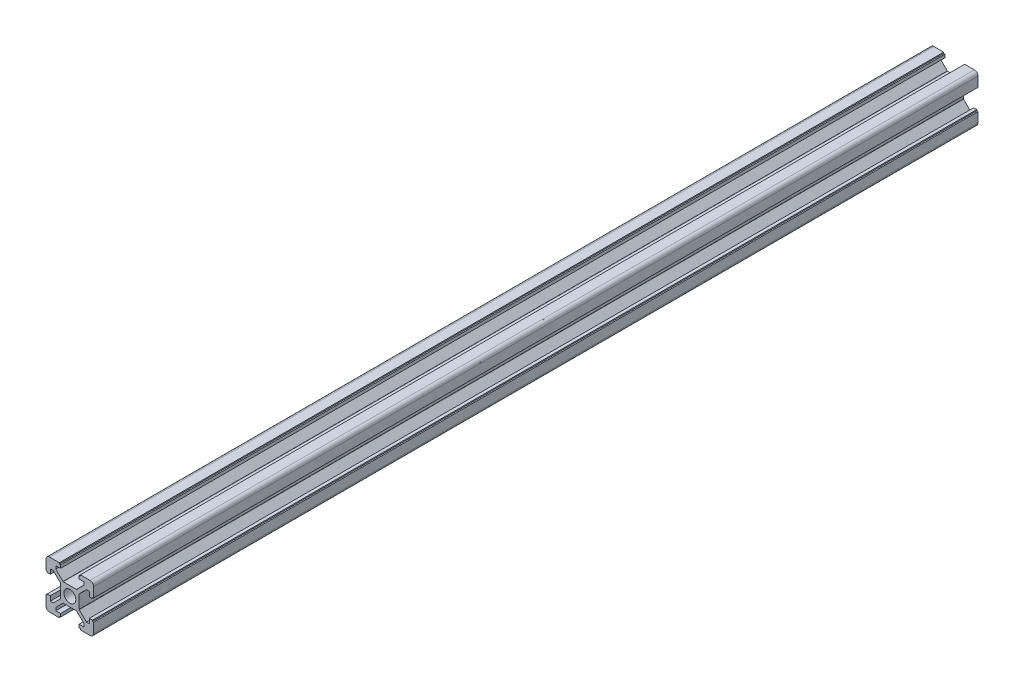
SolidWorks part; units mm, degrees
ref_plane "前视基准面" through (0, 0, 0) normal (0, 0, 1) x (1, 0, 0)
ref_plane "上视基准面" through (0, 0, 0) normal (0, 1, 0) x (1, 0, 0)
ref_plane "右视基准面" through (0, 0, 0) normal (1, 0, 0) x (0, 0, -1)
other "Configuration Table"
sketch "草图1" plane through (0, 0, 0) normal (0, 0, 1) x (1, 0, 0)
  line L0 (-10, 0) -> (10, 0) construction
  line L1 (-10, 10) -> (-4.4, 10)
  line L2 (-10, 10) -> (-10, 4.4)
  line L3 (-10, -10) -> (-4.4, -10)
  line L4 (10, 10) -> (10, 4.4)
  line L5 (-10, 10) -> (10, -10) construction
  line L6 (-10, -10) -> (10, 10) construction
  line L7 (-2.8396, 3.9001) -> (2.8395, 3.9001)
  line L8 (-3.9, 2.8393) -> (-3.9, -2.8395)
  line L9 (-2.8393, -3.9) -> (2.8395, -3.9)
  line L10 (3.9001, 2.8396) -> (3.9001, -2.8395)
  line L11 (-3.9, 3.9) -> (3.9, -3.9) construction
  line L12 (-3.9, -3.9) -> (3.9, 3.9) construction
  line L13 (0, 10) -> (0, -10) construction
  line L14 (-6.9607, 5.9) -> (-3.9, 2.8393)
  line L15 (-5.9, 6.9607) -> (-2.8396, 3.9001)
  line L16 (-6.9607, 5.9) -> (-8.2, 5.9)
  line L17 (-8.2, 5.9) -> (-8.2, 3.9)
  line L18 (-8.2, 3.9) -> (-9.5, 3.9)
  line L19 (-9.5, 3.9) -> (-9.5, 4.4)
  line L20 (-9.5, 4.4) -> (-10, 4.4)
  line L21 (-5.9, 6.9607) -> (-5.9, 8.2)
  line L22 (-5.9, 8.2) -> (-3.9, 8.2)
  line L23 (-3.9, 8.2) -> (-3.9, 9.5)
  line L24 (-3.9, 9.5) -> (-4.4, 9.5)
  line L25 (-4.4, 9.5) -> (-4.4, 10)
  line L26 (6.9607, 5.9) -> (3.9001, 2.8396)
  line L27 (5.9, 6.9607) -> (2.8393, 3.9)
  line L28 (5.9, 6.9607) -> (5.9, 8.2)
  line L29 (5.9, 8.2) -> (3.9, 8.2)
  line L30 (3.9, 8.2) -> (3.9, 9.5)
  line L31 (3.9, 9.5) -> (4.4, 9.5)
  line L32 (4.4, 9.5) -> (4.4, 10)
  line L33 (6.9607, 5.9) -> (8.2, 5.9)
  line L34 (8.2, 5.9) -> (8.2, 3.9)
  line L35 (8.2, 3.9) -> (9.5, 3.9)
  line L36 (9.5, 3.9) -> (9.5, 4.4)
  line L37 (9.5, 4.4) -> (10, 4.4)
  line L38 (5.9, -6.9607) -> (2.8395, -3.9)
  line L39 (6.9607, -5.9) -> (3.9, -2.8393)
  line L40 (6.9607, -5.9) -> (8.2, -5.9)
  line L41 (8.2, -5.9) -> (8.2, -3.9)
  line L42 (8.2, -3.9) -> (9.5, -3.9)
  line L43 (9.5, -3.9) -> (9.5, -4.4)
  line L44 (9.5, -4.4) -> (10, -4.4)
  line L45 (5.9, -6.9607) -> (5.9, -8.2)
  line L46 (5.9, -8.2) -> (3.9, -8.2)
  line L47 (3.9, -8.2) -> (3.9, -9.5)
  line L48 (3.9, -9.5) -> (4.4, -9.5)
  line L49 (4.4, -9.5) -> (4.4, -10)
  line L50 (-6.9607, -5.9) -> (-3.9, -2.8395)
  line L51 (-5.9, -6.9607) -> (-2.8393, -3.9)
  line L52 (-5.9, -6.9607) -> (-5.9, -8.2)
  line L53 (-5.9, -8.2) -> (-3.9, -8.2)
  line L54 (-3.9, -8.2) -> (-3.9, -9.5)
  line L55 (-3.9, -9.5) -> (-4.4, -9.5)
  line L56 (-4.4, -9.5) -> (-4.4, -10)
  line L57 (-6.9607, -5.9) -> (-8.2, -5.9)
  line L58 (-8.2, -5.9) -> (-8.2, -3.9)
  line L59 (-8.2, -3.9) -> (-9.5, -3.9)
  line L60 (-9.5, -3.9) -> (-9.5, -4.4)
  line L61 (-9.5, -4.4) -> (-10, -4.4)
  line L62 (4.4, -10) -> (10, -10)
  line L63 (-10, -4.4) -> (-10, -10)
  line L64 (10, -10) -> (10, -4.4)
  line L65 (4.4, 10) -> (10, 10)
  circle A0 centre (0, 0) radius 2.5
  point P0 (0, 0)
  point P6 (0, 0)
  point P76 (0, 0)
  dimension "D6" = 5
  dimension "D2" = 20
  dimension "D3" = 7.8
  dimension "D4" = 7.8
  dimension "D5" = 0.75
  dimension "D7" = 0.5
  dimension "D8" = 0.5
  dimension "D9" = 1.8
  dimension "D10" = 6.1
  dimension "D12" = 2
  dimension "D11" = 4
extrude "凸台-拉伸1" add sketch "草图1" along normal blind 371
fillet "圆角1" radius 1.5 4 edges at (10, -10, 185.5) (-10, -10, 185.5) (-10, 10, 185.5) (10, 10, 185.5)
fillet "圆角2" radius 0.2 8 edges at (3.9001, -2.8395, 185.5) (3.9001, 2.8396, 185.5) (-2.8393, -3.9, 185.5) (2.8395, -3.9, 185.5) (-2.8396, 3.9001, 185.5) (2.8395, 3.9001, 185.5) (-3.9, 2.8393, 185.5) (-3.9, -2.8395, 185.5)
